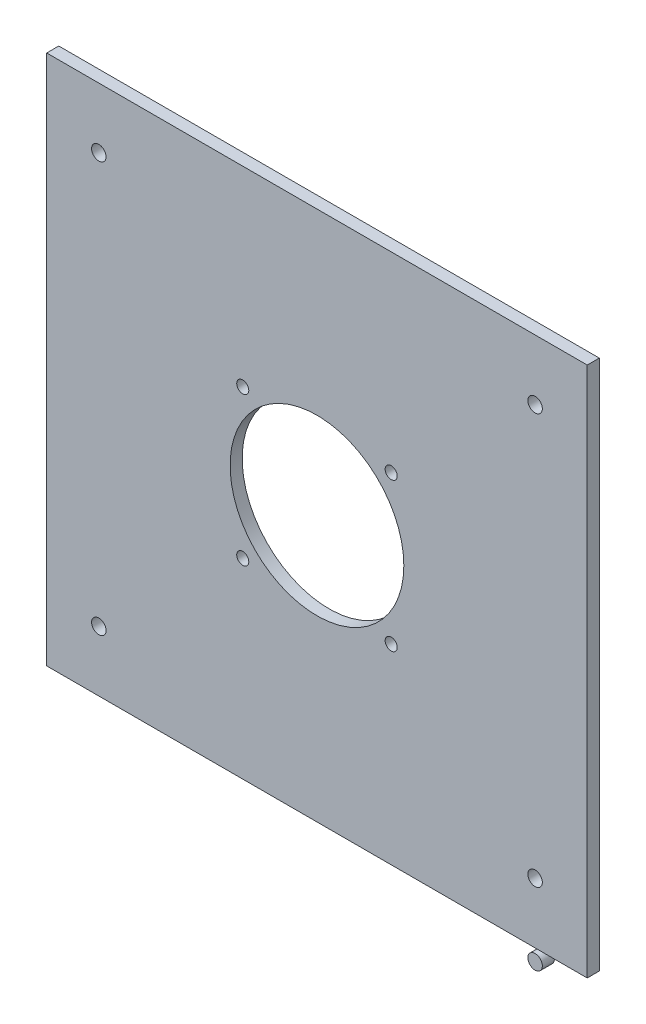
SolidWorks part; units mm, degrees
material "环氧树脂,未充填"
ref_plane "前视基准面" through (0, 0, 0) normal (0, 0, 1) x (1, 0, 0)
ref_plane "上视基准面" through (0, 0, 0) normal (0, 1, 0) x (1, 0, 0)
ref_plane "右视基准面" through (0, 0, 0) normal (1, 0, 0) x (0, 0, -1)
sketch "草图1" plane through (0, 0, 0) normal (0, 0, 1) x (1, 0, 0)
  line L0 (0, 0) -> (180.802, -180.802) construction
  line L1 (-560, -550) -> (560, -550)
  line L2 (-560, -550) -> (-560, 550)
  line L3 (-560, 550) -> (560, 550)
  line L4 (560, -550) -> (560, 550)
  line L5 (-560, -550) -> (560, 550) construction
  line L6 (-560, 550) -> (560, -550) construction
  line L8 (0, 350.0881) -> (0, -359.2962) construction
  line L9 (-153.7957, -153.7957) -> (0, 0) construction
  line L10 (-189.0671, -107.5169) -> (0, 0) construction
  circle A0 centre (-452, 425) radius 15
  circle A1 centre (0, 0) radius 180
  circle A2 centre (0, 0) radius 217.5 construction
  circle A3 centre (153.7957, -153.7957) radius 12.5
  circle A4 centre (-153.7957, -153.7957) radius 12.5
  circle A5 centre (-153.7957, 153.7957) radius 12.5
  circle A6 centre (153.7957, 153.7957) radius 12.5
  circle A7 centre (452, 425) radius 15
  circle A8 centre (452, -575) radius 15
  circle A10 centre (-452, -575) radius 15 [skipped]
  point P0 (0, 0)
  point P24 (0, 0)
  point P38 (0, 0)
  dimension "D3" = 30
  dimension "D6" = 360
  dimension "D7" = 435
  dimension "D9" = 25
  dimension "D5" = 904
  dimension "D4" = 1000
  dimension "D10" = 4
  dimension "D1" = 1120
  dimension "D2" = 1100
  dimension "D8" = 45
  dimension "D11" = 2
  dimension "D12" = 2
extrude "凸台-拉伸1" add sketch "草图1" along normal blind 25
sketch "草图2" plane through (0, 0, 0) normal (0, 0, -1) x (-1, 0, 0)
  circle A0 centre (452, -425) radius 15
extrude "切除-拉伸1" cut sketch "草图2" against normal through all
sketch "草图4" plane through (0, 0, 0) normal (0, 0, -1) x (-1, 0, 0)
  circle A0 centre (-452, -425) radius 15
extrude "切除-拉伸2" cut sketch "草图4" against normal through all
